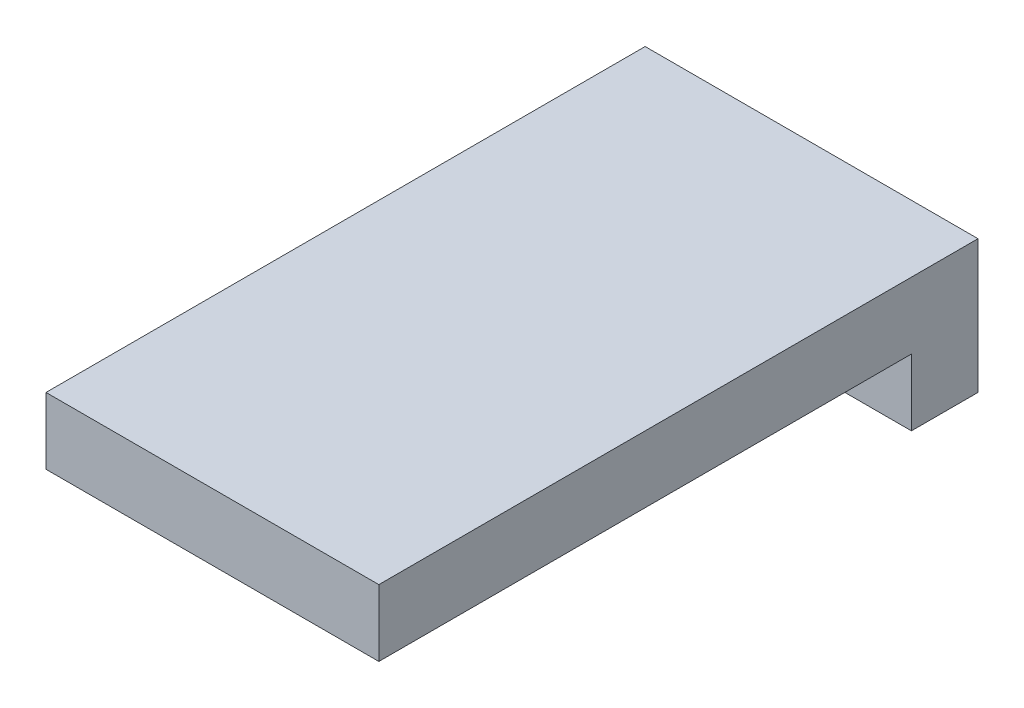
SolidWorks part; units mm, degrees
ref_plane "Front Plane" through (0, 0, 0) normal (0, 0, 1) x (1, 0, 0)
ref_plane "Top Plane" through (0, 0, 0) normal (0, 1, 0) x (1, 0, 0)
ref_plane "Right Plane" through (0, 0, 0) normal (1, 0, 0) x (0, 0, -1)
sketch "Sketch1" plane through (0, 0, 0) normal (0, 1, 0) x (1, 0, 0)
  line L1 (-12.5, 2.5) -> (12.5, 2.5)
  line L2 (-12.5, 2.5) -> (-12.5, -2.5)
  line L3 (-12.5, -2.5) -> (12.5, -2.5)
  line L4 (12.5, 2.5) -> (12.5, -2.5)
  line L5 (-12.5, 2.5) -> (12.5, -2.5) construction
  line L6 (-12.5, -2.5) -> (12.5, 2.5) construction
  point P0 (0, 0)
  dimension "D1" = 25
  dimension "D2" = 5
extrude "Boss-Extrude1" add sketch "Sketch1" along normal blind 10
sketch "Sketch2" plane through (0, 0, 2.5) normal (0, 0, 1) x (1, 0, 0)
  line L1 (12.5, 5) -> (-12.5, 5)
  line L2 (12.5, 5) -> (12.5, 10)
  line L3 (12.5, 10) -> (-12.5, 10)
  line L4 (-12.5, 5) -> (-12.5, 10)
  line L5 (12.5, 5) -> (-12.5, 10) construction
  line L6 (12.5, 10) -> (-12.5, 5) construction
  point P0 (0, 7.5)
  dimension "D1" = 5
extrude "Boss-Extrude2" add sketch "Sketch2" along normal blind 40
sketch "Sketch3" plane through (0, 5, 0) normal (0, -1, 0) x (1, 0, 0)
  line L1 (3.3293, 36.1977) -> (-3.6707, 36.1977)
  line L2 (3.3293, 36.1977) -> (3.3293, 38.6977)
  line L3 (3.3293, 38.6977) -> (-3.6707, 38.6977)
  line L4 (-3.6707, 36.1977) -> (-3.6707, 38.6977)
  line L5 (3.3293, 36.1977) -> (-3.6707, 38.6977) construction
  line L6 (3.3293, 38.6977) -> (-3.6707, 36.1977) construction
  point P0 (-0.1707, 37.4477)
  dimension "D1" = 7
  dimension "D2" = 2.5
extrude "Boss-Extrude3" add sketch "Sketch3" along normal blind 2.5
